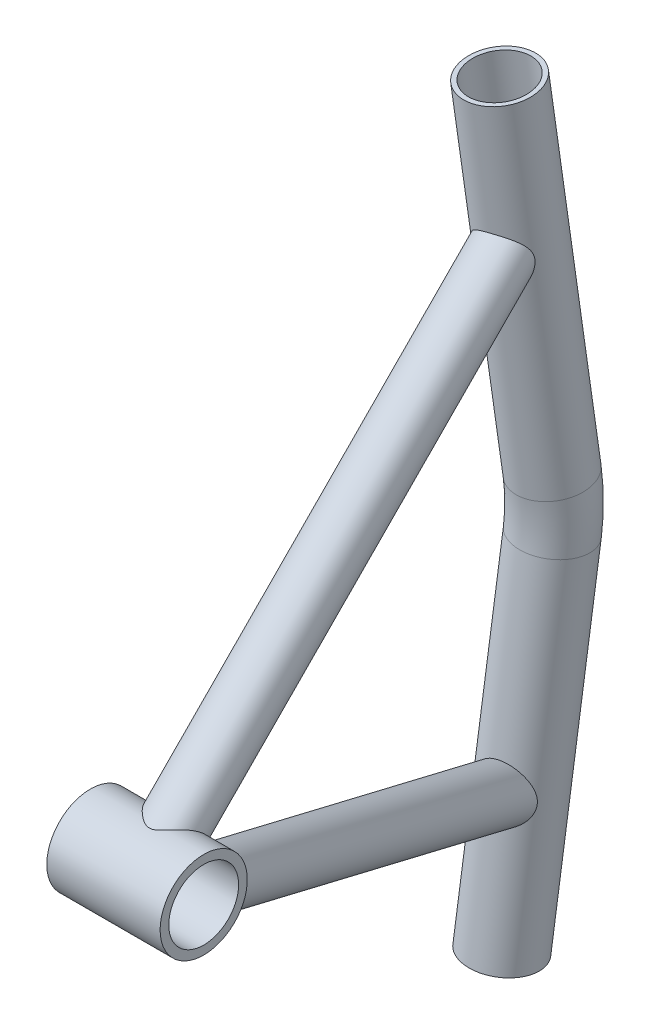
SolidWorks part; units mm, degrees
material "AISI 4130 Steel, normalized at 870C"
ref_plane "X-Y Datum" through (0, 0, 0) normal (0, 0, 1) x (1, 0, 0)
ref_plane "X-Z Datum" through (0, 0, 0) normal (0, 1, 0) x (1, 0, 0)
ref_plane "Y-Z Datum" through (0, 0, 0) normal (1, 0, 0) x (0, 0, -1)
ref_plane "FRH Reference" through (-89.8073, 0, -36.2845) normal (-0.9272, 0, -0.3746) x (-0.3746, 0, 0.9272)
sketch "Sketch6" plane through (0, 0, 0) normal (0, 1, 0) x (1, 0, 0)
  line L1 (20.6375, 15.875) -> (-20.6375, 15.875)
  line L2 (20.6375, 15.875) -> (20.6375, 12.7254)
  line L3 (20.6375, 12.7254) -> (-20.6375, 12.7254)
  line L4 (-20.6375, 15.875) -> (-20.6375, 12.7254)
  line L9 (-66.7868, 0) -> (90.4215, 0) construction
revolve "Revolve2" add sketch "Sketch6" angle 360 about L9
sketch3d "3DSketch2"
  line L0 (0, 0, 0) -> (0, 11.2253, -11.2253) construction
  line L1 (-66.7868, 0, 0) -> (90.4215, 0, 0) construction
  line L2 (0, 0, 0) -> (0, 0, 15.875) construction
  line L3 (0, 0, 0) -> (0, 0, -15.875) construction
  line L4 (0, 0, 0) -> (0, -11.2253, -11.2253) construction
  line L7 (20.6375, 0, -15.875) -> (-20.6375, 0, -15.875) construction
  line L8 (0, 11.2253, -11.2253) -> (-46.2575, 90.6875, -181.7726)
  line L9 (0, -11.2253, -11.2253) -> (-46.5923, -87.7798, -183.007)
  line L10 (-48.4118, 138.3511, -176.8193) -> (-42.6114, 10.0194, -190.1557)
  line L11 (-42.659, -9.2699, -190.2654) -> (-49.1309, -138.4519, -178.3222)
  line L12 (0, 0, 0) -> (86.995, 0, 0) construction
  arc A0 (-42.6114, 10.0194, -190.1557) -> (-42.659, -9.2699, -190.2654) centre (-81.2205, 0.0176, -110.7044) ccw
  point P20 (-161.1993, 0.4361, -149.5172)
  dimension "D1" = 45
  dimension "D2" = 135
  dimension "D3" = 45
  dimension "D4" = 135
  dimension "D5" = 193.7534
  dimension "D7" = 47.485
  dimension "D8" = 86.995
ref_plane "Plane1" through (-46.2575, 90.6875, -181.7726) normal (-0.2387, 0.4101, -0.8802) x (-0.9711, -0.099, 0.2172)
sketch "Sketch10" plane through (-46.2575, 90.6875, -181.7726) normal (-0.2387, 0.4101, -0.8802) x (-0.9711, -0.099, 0.2172)
  circle A0 centre (0, 0) radius 9.525
  circle A1 centre (0, 0) radius 7.874
  dimension "D1" = 19.05
  dimension "D2" = 1.651
extrude "Boss-Extrude1" add sketch "Sketch10" against normal up to surface (203.6414 mm away) separate body
ref_plane "Plane2" through (-46.5923, -87.7798, -183.007) normal (-0.2405, -0.3951, -0.8866) x (-0.9707, 0.0996, 0.2189)
sketch "Sketch11" plane through (-46.5923, -87.7798, -183.007) normal (-0.2405, -0.3951, -0.8866) x (-0.9707, 0.0996, 0.2189)
  circle A0 centre (0, 0) radius 9.525
  circle A1 centre (0, 0) radius 7.874
  dimension "D1" = 19.05
  dimension "D2" = 1.651
extrude "Boss-Extrude2" add sketch "Sketch11" against normal up to surface (193.1551 mm away) separate body
ref_plane "Plane3" through (-49.1309, -138.4519, -178.3222) normal (-0.0498, -0.9945, 0.0919) x (-0.9988, 0.0496, -0.0047)
sketch "Sketch12" plane through (-49.1309, -138.4519, -178.3222) normal (-0.0498, -0.9945, 0.0919) x (-0.9988, 0.0496, -0.0047)
  circle A0 centre (0, 0) radius 12.7
  dimension "D1" = 25.4
sweep "Cut-Sweep1" cut profiles "Sketch12" path "3DSketch2"
ref_plane "Plane4" through (-109.2195, 0.5715, -53.003) normal (0.8996, -0.0047, 0.4366) x (0.4366, 0, -0.8997)
sketch "Sketch14" plane through (-109.2195, 0.5715, -53.003) normal (0.8996, -0.0047, 0.4366) x (0.4366, 0, -0.8997)
  line L0 (137.9407, 137.7811) -> (152.4713, 9.448)
  line L1 (152.5492, -9.8416) -> (138.9787, -139.025)
  arc A0 (152.4713, 9.448) -> (152.5492, -9.8416) centre (64.1357, -0.5539) cw
sketch "Sketch15" plane through (-49.1309, -138.4519, -178.3222) normal (-0.0498, -0.9945, 0.0919) x (-0.9988, 0.0496, -0.0047)
  circle A0 centre (0, 0) radius 12.7
  circle A1 centre (0, 0) radius 11.049
  dimension "D1" = 25.4
  dimension "D2" = 1.651
sweep "Sweep2" add profiles "Sketch15" path "Sketch14"
equation "\"Tube_Thickness\"=0.75"
equation "\"Wall_Thickness\"=0.065"
